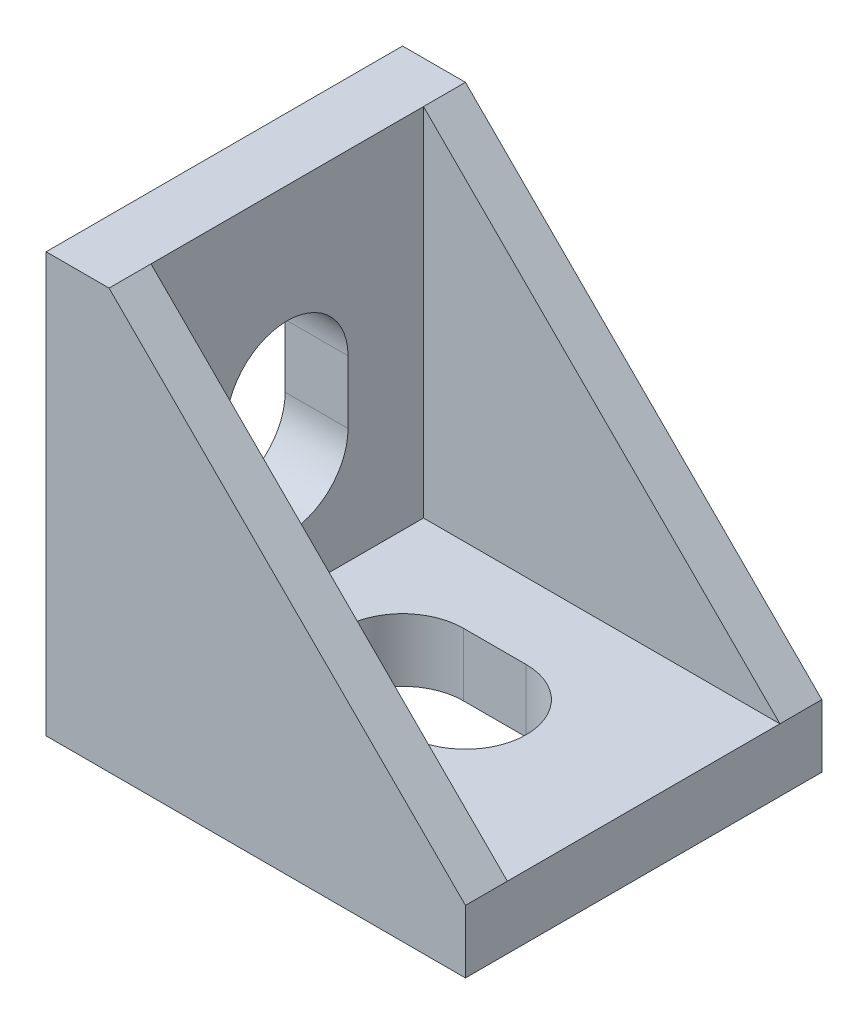
SolidWorks part; units mm, degrees
material "6061-T6 (SS)"
ref_plane "Front Plane" through (0, 0, 0) normal (0, 0, 1) x (1, 0, 0)
ref_plane "Top Plane" through (0, 0, 0) normal (0, 1, 0) x (1, 0, 0)
ref_plane "Right Plane" through (0, 0, 0) normal (1, 0, 0) x (0, 0, -1)
sketch "Sketch1" plane through (0, 0, 0) normal (0, 0, 1) x (1, 0, 0)
  line L0 (0, 0) -> (0, 20)
  line L1 (0, 20) -> (3, 20)
  line L2 (3, 20) -> (20, 3)
  line L3 (20, 3) -> (20, 0)
  line L4 (20, 0) -> (0, 0)
  dimension "D1" = 20
  dimension "D2" = 3
  dimension "D3" = 3
  dimension "D4" = 20
extrude "Boss-Extrude1" add sketch "Sketch1" along normal mid plane 17
sketch "Sketch2" plane through (0, 0, 8.5) normal (0, 0, 1) x (1, 0, 0)
  line L0 (3, 20) -> (3, 3)
  line L2 (20, 3) -> (3, 3)
  line L4 (3, 20) -> (20, 3)
extrude "Cut-Extrude1" cut sketch "Sketch2" against normal blind 13 from offset 2 offset against normal yes
sketch "Sketch3" plane through (3, 0, 0) normal (1, 0, 0) x (0, 0, -1)
  line L0 (0, 11.5) -> (0, 8.5) construction
  line L1 (2.9, 11.5) -> (2.9, 8.5)
  line L2 (-2.9, 11.5) -> (-2.9, 8.5)
  line L3 (6.5, 20) -> (-6.5, 20) construction
  arc A0 (2.9, 11.5) -> (-2.9, 11.5) centre (0, 11.5) ccw
  arc A1 (-2.9, 8.5) -> (2.9, 8.5) centre (0, 8.5) ccw
  point P3 (0, 10)
  dimension "D3" = 2.9
  dimension "D1" = 8.5
  dimension "D2" = 3
extrude "Cut-Extrude2" cut sketch "Sketch3" against normal through all
sketch "Sketch4" plane through (0, 3, 0) normal (0, 1, 0) x (1, 0, 0)
  line L0 (11.5, 0) -> (8.5, 0) construction
  line L1 (11.5, -2.9) -> (8.5, -2.9)
  line L2 (11.5, 2.9) -> (8.5, 2.9)
  line L3 (20, 6.5) -> (20, -6.5) construction
  arc A0 (11.5, -2.9) -> (11.5, 2.9) centre (11.5, 0) ccw
  arc A1 (8.5, 2.9) -> (8.5, -2.9) centre (8.5, 0) ccw
  point P3 (10, 0)
  dimension "D1" = 2.9
  dimension "D2" = 8.5
  dimension "D3" = 3
extrude "Cut-Extrude3" cut sketch "Sketch4" against normal through all
sketch "Sketch5" plane through (0, 0, 0) normal (-1, 0, 0) x (0, 0, 1)
  line L0 (8.5, 20) -> (-8.5, 20) construction
  line L1 (-2, 18.5) -> (2, 18.5)
  line L2 (-2, 18.5) -> (-2, 16.65)
  line L3 (-2, 16.65) -> (2, 16.65)
  line L4 (2, 18.5) -> (2, 16.65)
  line L5 (-2, 18.5) -> (2, 16.65) construction
  line L6 (-2, 16.65) -> (2, 18.5) construction
  line L8 (-8.5, 10) -> (8.5, 10) construction
  line L9 (-8.5, 20) -> (-8.5, 0) construction
  line L10 (8.5, 20) -> (8.5, 0) construction
  line L11 (-2, 3.35) -> (2, 1.5) construction
  line L12 (-2, 1.5) -> (2, 3.35) construction
  line L13 (2, 1.5) -> (2, 3.35)
  line L14 (-2, 3.35) -> (2, 3.35)
  line L15 (-2, 1.5) -> (-2, 3.35)
  line L16 (-2, 1.5) -> (2, 1.5)
  point P0 (0, 17.575)
  point P8 (0, 20)
  point P18 (0, 2.425)
  dimension "D1" = 4
  dimension "D2" = 1.5
  dimension "D3" = 1.85
extrude "Boss-Extrude2" add sketch "Sketch5" along normal blind 1
